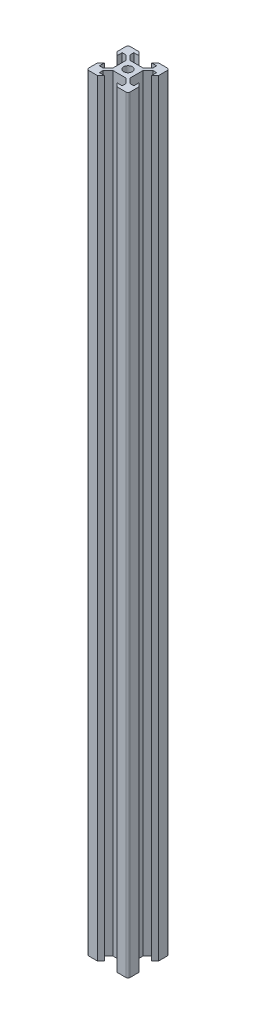
SolidWorks part; units mm, degrees
material "1060 Alloy"
ref_plane "Front Plane" through (0, 0, 0) normal (0, 0, 1) x (1, 0, 0)
ref_plane "Top Plane" through (0, 0, 0) normal (0, 1, 0) x (1, 0, 0)
ref_plane "Right Plane" through (0, 0, 0) normal (1, 0, 0) x (0, 0, -1)
ref_plane "End Plane" through (0, 370, 0) normal (0, 1, 0) x (1, 0, 0)
sketch "MasterLayoutSketch" plane through (0, 0, 0) normal (0, 1, 0) x (1, 0, 0)
  line L0 (-8.325, 3.1) -> (-8.325, 5.5)
  line L1 (-10, -10) -> (10, -10) construction
  line L2 (-10, -10) -> (-10, 10) construction
  line L3 (-10, 10) -> (10, 10) construction
  line L4 (10, -10) -> (10, 10) construction
  line L5 (-10, -10) -> (10, 10) construction
  line L6 (-10, 10) -> (10, -10) construction
  line L7 (-4.775, 10) -> (-3.1, 8.325)
  line L10 (-8.325, 5.5) -> (-6.5607, 5.5)
  line L11 (-10, 4.775) -> (-8.325, 3.1)
  line L12 (-5.5, 8.325) -> (-5.5, 6.5607)
  line L13 (-3.1, 8.325) -> (-5.5, 8.325)
  line L14 (-10, 10) -> (-10, 4.775)
  line L19 (3.1, 8.325) -> (5.5, 8.325)
  line L20 (10, 4.775) -> (8.325, 3.1)
  line L21 (-10, 10) -> (-4.775, 10)
  line L22 (-6.5607, 5.5) -> (-4.1607, 3.1)
  line L23 (-5.5, 6.5607) -> (-3.1, 4.1607)
  line L24 (5.5, 8.325) -> (5.5, 6.5607)
  line L25 (4.775, 10) -> (3.1, 8.325)
  line L26 (8.325, 5.5) -> (6.5607, 5.5)
  line L27 (8.325, 3.1) -> (8.325, 5.5)
  line L28 (10, 10) -> (4.775, 10)
  line L29 (10, 10) -> (10, 4.775)
  line L30 (5.5, 6.5607) -> (3.1, 4.1607)
  line L31 (6.5607, 5.5) -> (4.1607, 3.1)
  line L32 (8.325, -3.1) -> (8.325, -5.5)
  line L33 (4.775, -10) -> (3.1, -8.325)
  line L34 (8.325, -5.5) -> (6.5607, -5.5)
  line L35 (10, -4.775) -> (8.325, -3.1)
  line L36 (5.5, -8.325) -> (5.5, -6.5607)
  line L37 (3.1, -8.325) -> (5.5, -8.325)
  line L38 (10, -10) -> (10, -4.775)
  line L39 (10, -10) -> (4.775, -10)
  line L40 (6.5607, -5.5) -> (4.1607, -3.1)
  line L41 (5.5, -6.5607) -> (3.1, -4.1607)
  line L42 (-3.1, -8.325) -> (-5.5, -8.325)
  line L43 (-10, -4.775) -> (-8.325, -3.1)
  line L44 (-5.5, -8.325) -> (-5.5, -6.5607)
  line L45 (-4.775, -10) -> (-3.1, -8.325)
  line L46 (-8.325, -5.5) -> (-6.5607, -5.5)
  line L47 (-8.325, -3.1) -> (-8.325, -5.5)
  line L48 (-10, -10) -> (-4.775, -10)
  line L49 (-10, -10) -> (-10, -4.775)
  line L50 (-5.5, -6.5607) -> (-3.1, -4.1607)
  line L51 (-6.5607, -5.5) -> (-4.1607, -3.1)
  line L52 (-4.1607, 3.1) -> (-4.1607, -3.1)
  line L53 (-3.1, -4.1607) -> (3.1, -4.1607)
  line L54 (4.1607, -3.1) -> (4.1607, 3.1)
  line L55 (-3.1, 4.1607) -> (3.1, 4.1607)
  circle A0 centre (0, 0) radius 2.1
  point P0 (0, 0)
  point P9 (0, 0)
  dimension "D6" = 4.2
  dimension "D1" = 20
  dimension "D2" = 4
  dimension "D3" = 11
  dimension "D4" = 9.55
  dimension "D5" = 6.2
  dimension "D7" = 1.5
extrude "Main Extrusion" add sketch "MasterLayoutSketch" along normal up to surface (370 mm away) up to plane "End Plane"
fillet "Edge Fillets" radius 1 4 edges at (10, 185, -10) (10, 185, 10) (-10, 185, 10) (-10, 185, -10)
